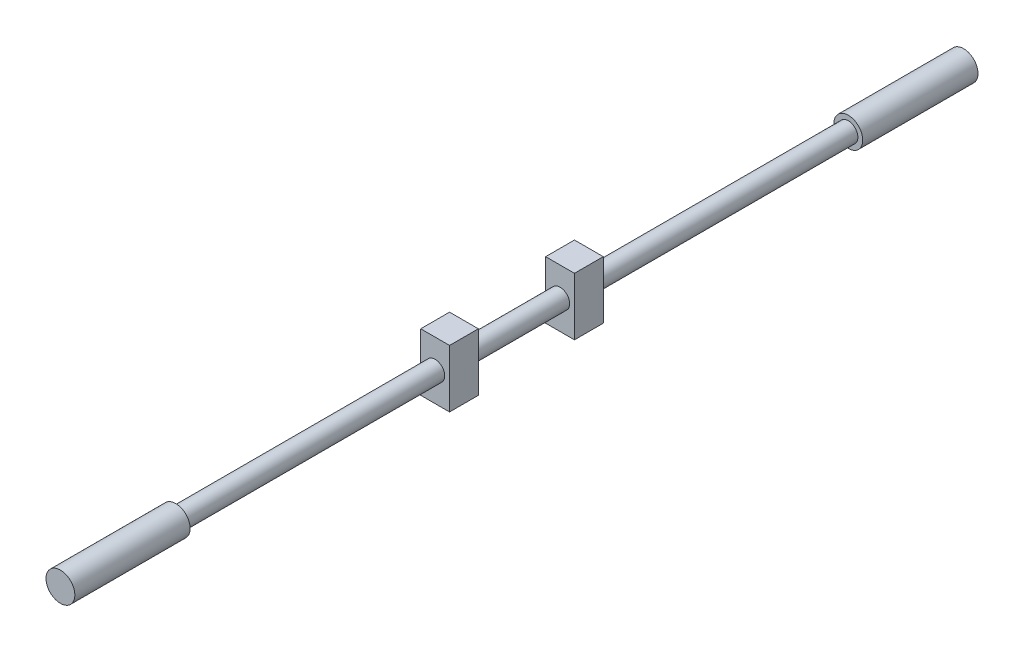
SolidWorks part; units mm, degrees
ref_plane "Front Plane" through (0, 0, 0) normal (0, 0, 1) x (1, 0, 0)
ref_plane "Top Plane" through (0, 0, 0) normal (0, 1, 0) x (1, 0, 0)
ref_plane "Right Plane" through (0, 0, 0) normal (1, 0, 0) x (0, 0, -1)
sketch "Sketch1" plane through (0, 0, 0) normal (0, 0, 1) x (1, 0, 0)
  circle A0 centre (0, 0) radius 25.4
  dimension "D1" = 50.8
extrude "Boss-Extrude1" add sketch "Sketch1" along normal blind 1778
sketch "Sketch2" plane through (0, 0, 1778) normal (0, 0, 1) x (1, 0, 0)
  circle A0 centre (0, 0) radius 38.1
extrude "Boss-Extrude2" add sketch "Sketch2" along normal blind 304.8
sketch "Sketch3" plane through (0, 0, 0) normal (0, 0, -1) x (-1, 0, 0)
  circle A0 centre (0, 0) radius 38.1
extrude "Boss-Extrude3" add sketch "Sketch3" along normal blind 304.8
sketch "Sketch4" plane through (0, 0, 0) normal (0, 1, 0) x (1, 0, 0)
  line L0 (-25.4, 0) -> (-25.4, -1778) construction
  line L6 (-38.1, -1016) -> (38.1, -1016)
  line L7 (-38.1, -1016) -> (-38.1, -1092.2)
  line L8 (-38.1, -1092.2) -> (38.1, -1092.2)
  line L9 (38.1, -1016) -> (38.1, -1092.2)
  line L10 (-38.1, -685.8) -> (38.1, -685.8)
  line L11 (-38.1, -685.8) -> (-38.1, -762)
  line L12 (-38.1, -762) -> (38.1, -762)
  line L13 (38.1, -685.8) -> (38.1, -762)
  line L14 (-38.1, 0) -> (38.1, 0) construction
  line L15 (38.1, -1778) -> (-38.1, -1778) construction
  dimension "D1" = 685.8
  dimension "D2" = 685.8
  dimension "D4" = 76.2
  dimension "D5" = 12.7
  dimension "D6" = 76.2
  dimension "D7" = 76.2
  dimension "D8" = 12.7
  dimension "D9" = 76.2
extrude "Boss-Extrude4" add sketch "Sketch4" along normal mid plane 152.4
